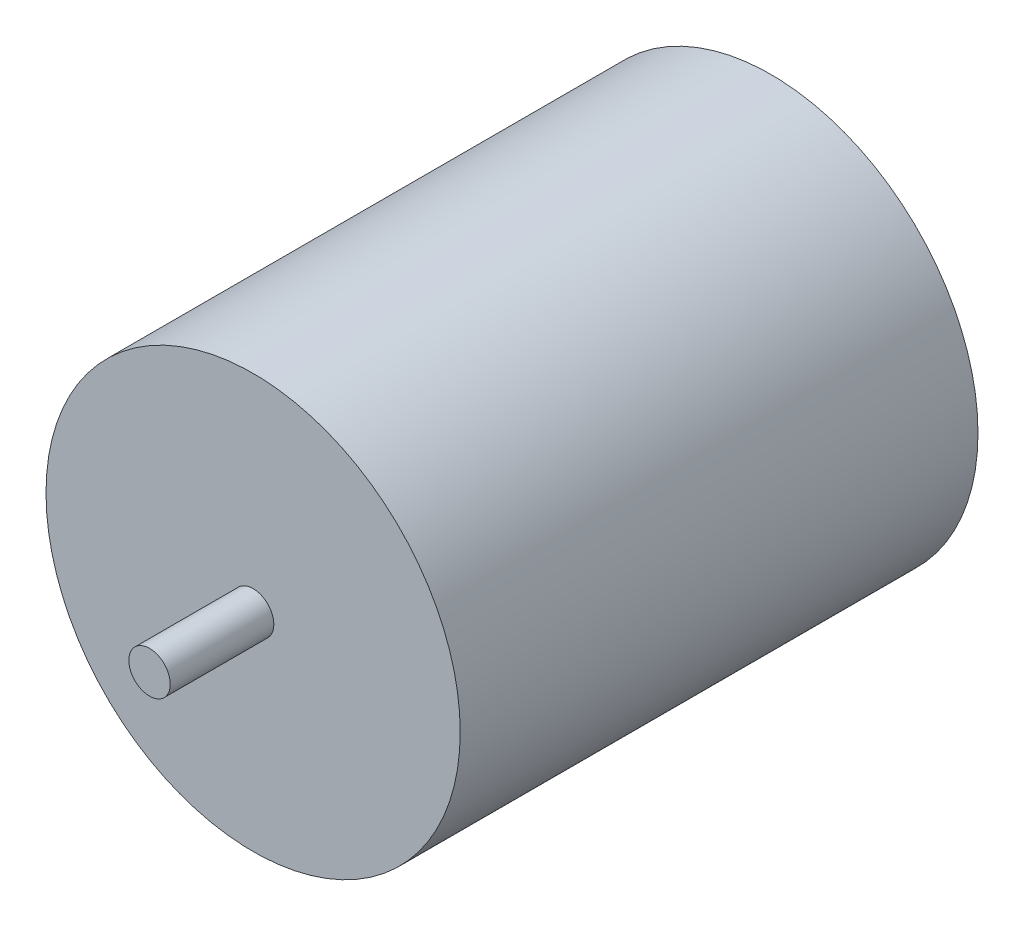
SolidWorks part; units mm, degrees
ref_plane "Front Plane" through (0, 0, 0) normal (0, 0, 1) x (1, 0, 0)
ref_plane "Top Plane" through (0, 0, 0) normal (0, 1, 0) x (1, 0, 0)
ref_plane "Right Plane" through (0, 0, 0) normal (1, 0, 0) x (0, 0, -1)
sketch "Sketch1" plane through (0, 0, 0) normal (0, 0, 1) x (1, 0, 0)
  circle A0 centre (0, 0) radius 12.7
  dimension "D1" = 25.4
extrude "Boss-Extrude1" add sketch "Sketch1" along normal blind 31.75 contours A0
sketch "Sketch2" plane through (0, 0, 31.75) normal (0, 0, 1) x (1, 0, 0)
  circle A0 centre (0, 0) radius 1.27
  dimension "D1" = 2.54
extrude "Boss-Extrude2" add sketch "Sketch2" along normal blind 6.35
equation "\"MotorLength\" = 1.25"
equation "\"MotorDiameter\" = 1"
equation "\"ShaftLength\"= 0.25"
equation "\"ShaftDiameter\"= 0.1"
equation "\"D1@Sketch1\"= \"MotorDiameter\""
equation "\"D1@Boss-Extrude1\"= \"MotorLength\""
equation "\"D1@Sketch2\"= \"ShaftDiameter\""
equation "\"D1@Boss-Extrude2\"= \"ShaftLength\""
